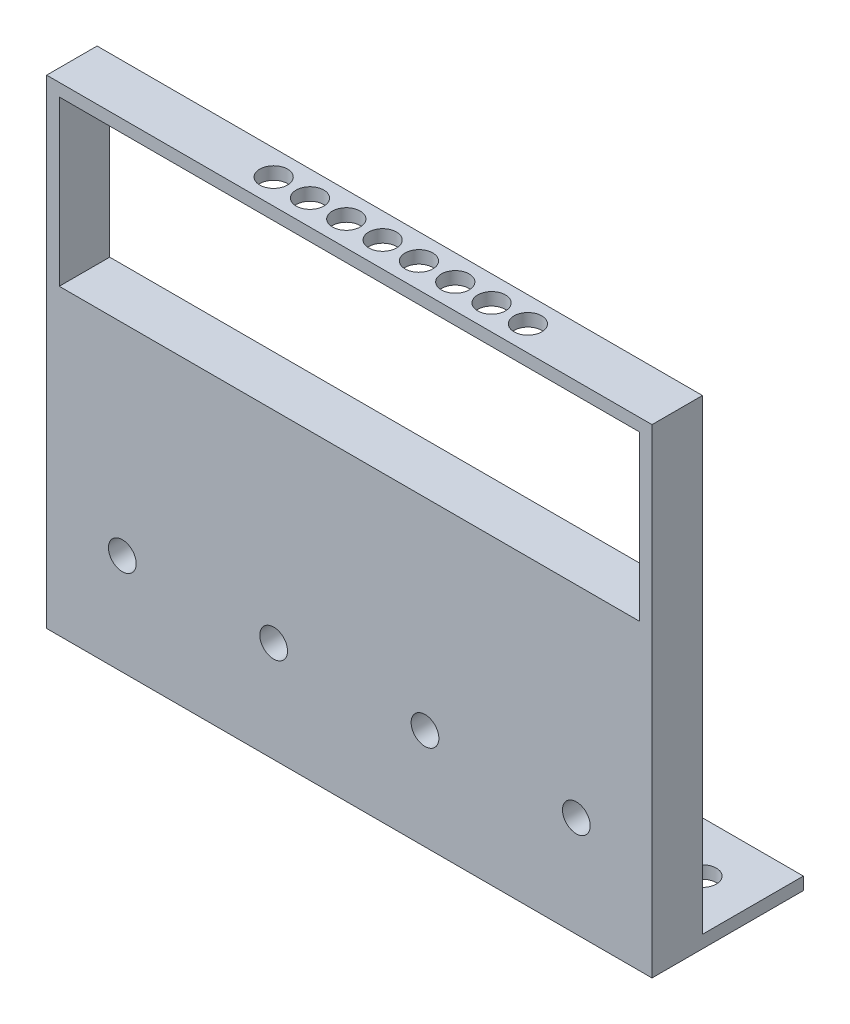
SolidWorks part; units mm, degrees
ref_plane "Front Plane" through (0, 0, 0) normal (0, 0, 1) x (1, 0, 0)
ref_plane "Top Plane" through (0, 0, 0) normal (0, 1, 0) x (1, 0, 0)
ref_plane "Right Plane" through (0, 0, 0) normal (1, 0, 0) x (0, 0, -1)
sketch "Sketch1" plane through (0, 0, 0) normal (0, 1, 0) x (1, 0, 0)
  line L1 (-76.2, -6.35) -> (76.2, -6.35)
  line L2 (-76.2, -6.35) -> (-76.2, 6.35)
  line L3 (-76.2, 6.35) -> (76.2, 6.35)
  line L4 (76.2, -6.35) -> (76.2, 6.35)
  line L5 (-76.2, -6.35) -> (76.2, 6.35) construction
  line L6 (-76.2, 6.35) -> (76.2, -6.35) construction
  point P0 (0, 0)
  dimension "D1" = 12.7
  dimension "D2" = 152.4
extrude "Boss-Extrude1" add sketch "Sketch1" along normal blind 76.2
sketch "Sketch2" plane through (0, 0, 0) normal (0, 1, 0) x (1, 0, 0)
  line L0 (-76.2, 6.35) -> (-76.2, -6.35) construction
  line L1 (-76.2, 19.05) -> (-76.2, 6.35)
  line L2 (-76.2, 6.35) -> (76.2, 6.35)
  line L3 (76.2, 31.75) -> (-76.2, 31.75)
  line L4 (-76.2, 19.05) -> (-76.2, 31.75)
  line L5 (0, 0) -> (-76.2, 31.75) construction
  line L6 (76.2, 31.75) -> (0, 0) construction
  line L7 (76.2, 6.35) -> (-76.2, 6.35) construction
  line L8 (-23.5905, 31.75) -> (-23.5905, 6.35) construction
  line L9 (-23.5905, 19.05) -> (-76.2, 19.05) construction
  line L10 (76.2, 6.35) -> (76.2, 31.75)
  circle A0 centre (-63.5, 19.05) radius 3.4925
  circle A1 centre (-38.1, 19.05) radius 3.4925
  circle A2 centre (-12.7, 19.05) radius 3.4925
  circle A3 centre (12.7, 19.05) radius 3.4925
  circle A4 centre (38.1, 19.05) radius 3.4925
  circle A5 centre (63.5, 19.05) radius 3.4925
  point P0 (0, 0)
  dimension "D2" = 6.985
  dimension "D1" = 25.4
  dimension "D3" = 6
  dimension "D4" = 12.7
extrude "Boss-Extrude4" add sketch "Sketch2" along normal blind 3.175
sketch "Sketch3" plane through (0, 0, 6.35) normal (0, 0, 1) x (1, 0, 0)
  line L0 (-76.2, 76.2) -> (-76.2, 120.65)
  line L1 (-76.2, 120.65) -> (76.2, 120.65)
  line L2 (76.2, 120.65) -> (76.2, 76.2)
  line L3 (76.2, 76.2) -> (76.2, 0) construction
  line L4 (-76.2, 76.2) -> (-76.2, 0) construction
  line L5 (76.2, 76.2) -> (73.025, 76.2)
  line L6 (-76.2, 76.2) -> (76.2, 76.2) construction
  line L7 (73.025, 76.2) -> (73.025, 117.475)
  line L8 (73.025, 117.475) -> (-73.025, 117.475)
  line L9 (-73.025, 117.475) -> (-73.025, 76.2)
  line L10 (-73.025, 76.2) -> (-76.2, 76.2)
  line L11 (-73.025, 117.475) -> (-73.025, 120.65) construction
  dimension "D1" = 3.175
  dimension "D2" = 44.45
extrude "Boss-Extrude5" add sketch "Sketch3" against normal up to surface (12.7 mm away) up to face at (0, 39.6875, -6.35)
sketch "Sketch4" plane through (0, 120.65, 0) normal (0, 1, 0) x (1, 0, 0)
  line L0 (-76.2, 6.35) -> (-76.2, -6.35) construction
  circle A0 centre (-25.4, 0) radius 3.4925
  circle A1 centre (-16.256, 0) radius 3.4925
  circle A2 centre (-7.112, 0) radius 3.4925
  circle A3 centre (2.032, 0) radius 3.4925
  circle A4 centre (11.176, 0) radius 3.4925
  circle A5 centre (20.32, 0) radius 3.4925
  circle A6 centre (29.464, 0) radius 3.4925
  circle A7 centre (38.608, 0) radius 3.4925
  dimension "D1" = 6.985
  dimension "D2" = 50.8
  dimension "D4" = 9.144
  dimension "D3" = 8
extrude "Cut-Extrude1" cut sketch "Sketch4" against normal up to next
sketch "Sketch5" plane through (0, 0, 0) normal (0, 0, 1) x (1, 0, 0)
  line L0 (-76.2, 120.65) -> (-76.2, 0) construction
  line L1 (-76.2, 0) -> (76.2, 0) construction
  circle A0 centre (-57.15, 25.4) radius 3.4925
  circle A1 centre (-19.05, 25.4) radius 3.4925
  circle A2 centre (19.05, 25.4) radius 3.4925
  circle A3 centre (57.15, 25.4) radius 3.4925
  dimension "D1" = 6.985
  dimension "D2" = 19.05
  dimension "D3" = 25.4
  dimension "D4" = 4
extrude "Cut-Extrude2" cut sketch "Sketch5" against normal through all both and the other way through all
